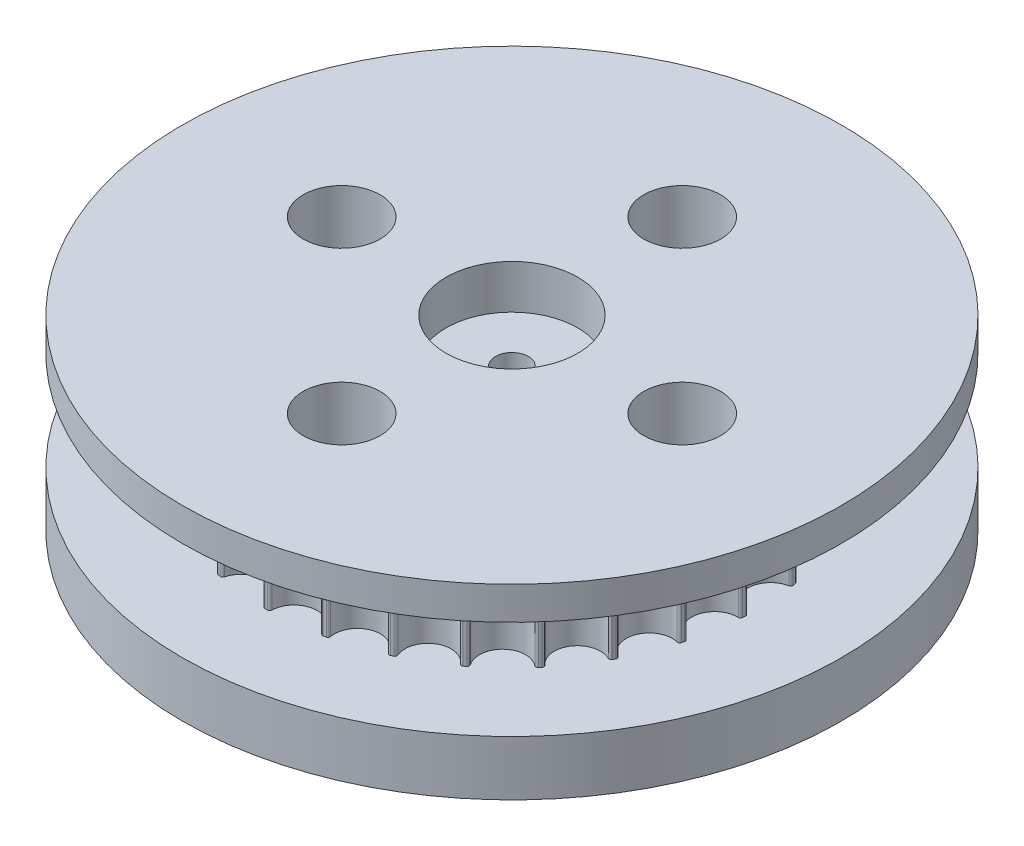
SolidWorks part; units mm, degrees
ref_plane "Front" through (0, 0, 0) normal (0, 0, 1) x (1, 0, 0)
ref_plane "Top" through (0, 0, 0) normal (0, 1, 0) x (1, 0, 0)
ref_plane "Right" through (0, 0, 0) normal (1, 0, 0) x (0, 0, -1)
sketch "Sketch1" plane through (0, 0, 0) normal (0, 1, 0) x (1, 0, 0)
  line L0 (0, 0) -> (0, 15.5) construction
  line L1 (0, 0) -> (15.5, 0) construction
  line L2 (0, 0) -> (0, -15.5) construction
  line L3 (0, 0) -> (-15.5, 0) construction
  circle A0 centre (0, 0) radius 30
  circle A1 centre (0, 0) radius 15.5 construction
  circle A2 centre (0, 15.5) radius 1.5
  circle A3 centre (15.5, 0) radius 1.5
  circle A4 centre (0, -15.5) radius 1.5
  circle A5 centre (-15.5, 0) radius 1.5
  circle A6 centre (0, 0) radius 1.5
  point P14 (0, 0)
  dimension "D1" = 60
  dimension "D2" = 31
  dimension "D3" = 3
  dimension "D5" = 3
  dimension "D4" = 4
extrude "Boss-Extrude1" add sketch "Sketch1" along normal blind 5
sketch "Sketch2" plane through (0, 5, 0) normal (0, 1, 0) x (1, 0, 0)
  line L0 (0, 0) -> (0, 15.5) construction
  line L1 (0, 0) -> (15.5, 0) construction
  line L2 (0, 0) -> (0, -15.5) construction
  line L3 (0, 0) -> (-15.5, 0) construction
  line L4 (0, 0) -> (0, 22.3727) construction
  line L5 (0, 0) -> (4.9707, 22.5821) construction
  line L6 (0, 0) -> (9.709, 20.9856) construction
  line L7 (0, 0) -> (13.9932, 18.4078) construction
  line L8 (0, 0) -> (17.6232, 14.9693) construction
  line L9 (0, 0) -> (20.4292, 10.8309) construction
  line L10 (0, 0) -> (22.2798, 6.186) construction
  line L11 (0, 0) -> (23.0888, 1.2518) construction
  line L12 (0, 0) -> (22.8181, -3.7408) construction
  line L13 (0, 0) -> (21.4804, -8.5586) construction
  line L14 (0, 0) -> (19.1384, -12.9761) construction
  line L15 (0, 0) -> (15.9014, -16.787) construction
  line L16 (0, 0) -> (11.921, -19.8128) construction
  line L17 (0, 0) -> (7.3831, -21.9123) construction
  line L18 (0, 0) -> (2.5, -22.9871) construction
  line L19 (0, 0) -> (-2.5, -22.9871) construction
  line L20 (0, 0) -> (-7.3831, -21.9123) construction
  line L21 (0, 0) -> (-11.921, -19.8128) construction
  line L22 (0, 0) -> (-15.9014, -16.787) construction
  line L23 (0, 0) -> (-19.1384, -12.9761) construction
  line L24 (0, 0) -> (-21.4804, -8.5586) construction
  line L25 (0, 0) -> (-22.0779, -3.6195) construction
  line L26 (0, 0) -> (-23.0888, 1.2518) construction
  line L27 (0, 0) -> (-22.2798, 6.186) construction
  line L28 (0, 0) -> (-20.4292, 10.8309) construction
  line L29 (0, 0) -> (-17.6232, 14.9693) construction
  line L30 (0, 0) -> (-13.9932, 18.4078) construction
  line L31 (0, 0) -> (-9.709, 20.9856) construction
  line L32 (0, 0) -> (-4.9707, 22.5821) construction
  line L33 (2.2986, 22.2543) -> (2.5392, 22.2281)
  line L34 (7.0288, 21.2399) -> (7.2582, 21.1626)
  line L35 (11.4304, 19.2323) -> (11.6379, 19.1075)
  line L36 (15.2976, 16.3255) -> (15.4733, 16.159)
  line L37 (18.4494, 12.6552) -> (18.5853, 12.4549)
  line L38 (20.7386, 8.3933) -> (20.8282, 8.1684)
  line L39 (22.058, 3.7389) -> (22.0972, 3.5)
  line L40 (22.3461, -1.0904) -> (22.333, -1.3321)
  line L41 (21.5892, -5.8686) -> (21.5245, -6.1019)
  line L42 (19.8229, -10.3725) -> (19.7095, -10.5863)
  line L43 (17.1297, -14.3913) -> (16.973, -14.5758)
  line L44 (13.6355, -17.7372) -> (13.4428, -17.8837)
  line L45 (9.5037, -20.2538) -> (9.2841, -20.3554)
  line L46 (4.9276, -21.8233) -> (4.6912, -21.8753)
  line L47 (0.121, -22.3723) -> (-0.121, -22.3723)
  line L48 (-4.6912, -21.8753) -> (-4.9276, -21.8233)
  line L49 (-9.2841, -20.3554) -> (-9.5037, -20.2538)
  line L50 (-13.4428, -17.8837) -> (-13.6355, -17.7372)
  line L51 (-16.973, -14.5758) -> (-17.1297, -14.3913)
  line L52 (-19.7095, -10.5863) -> (-19.8229, -10.3725)
  line L53 (-21.5245, -6.1019) -> (-21.5892, -5.8686)
  line L54 (-22.333, -1.3321) -> (-22.3461, -1.0904)
  line L55 (-22.0972, 3.5) -> (-22.058, 3.7389)
  line L56 (-20.8282, 8.1684) -> (-20.7386, 8.3933)
  line L57 (-18.5853, 12.4549) -> (-18.4494, 12.6552)
  line L58 (-15.4733, 16.159) -> (-15.2976, 16.3255)
  line L59 (-11.6379, 19.1075) -> (-11.4304, 19.2323)
  line L60 (-7.2582, 21.1626) -> (-7.0288, 21.2399)
  line L61 (-2.5392, 22.2281) -> (-2.2986, 22.2543)
  line L62 (0, 22.3727) -> (0, 23.8727) construction
  line L63 (4.8095, 21.8496) -> (4.9707, 22.5821) construction
  circle A0 centre (0, 15.5) radius 1.5
  circle A1 centre (0, 15.5) radius 1.5 construction
  circle A2 centre (15.5, 0) radius 1.5
  circle A3 centre (0, -15.5) radius 1.5
  circle A4 centre (-15.5, 0) radius 1.5
  circle A5 centre (0, 0) radius 20.2727 construction
  circle A6 centre (0, 0) radius 23.8727 construction
  circle A7 centre (0, 0) radius 22.3727 construction
  arc A8 (-2.0977, 22.2741) -> (2.0977, 22.2741) centre (0, 22.3727) ccw construction
  arc A9 (-2.2986, 22.2543) -> (-2.0799, 22.0829) centre (-2.278, 22.0553) cw
  arc A10 (2.2986, 22.2543) -> (2.0799, 22.0829) centre (2.278, 22.0553) ccw
  arc A11 (-2.0799, 22.0829) -> (2.0799, 22.0829) centre (0, 22.3727) ccw
  arc A12 (2.5392, 22.2281) -> (2.7159, 22.0138) centre (2.5165, 22.0294) cw
  arc A13 (2.7159, 22.0138) -> (6.7785, 21.1195) centre (4.8095, 21.8496) ccw
  arc A14 (7.0288, 21.2399) -> (6.7785, 21.1195) centre (6.966, 21.05) ccw
  arc A15 (7.2582, 21.1626) -> (7.3847, 20.9153) centre (7.1933, 20.9734) cw
  arc A16 (7.3847, 20.9153) -> (11.1601, 19.1686) centre (9.394, 20.3049) ccw
  arc A17 (11.4304, 19.2323) -> (11.1601, 19.1686) centre (11.3283, 19.0604) ccw
  arc A18 (11.6379, 19.1075) -> (11.7082, 18.8388) centre (11.5338, 18.9367) cw
  arc A19 (11.7082, 18.8388) -> (15.0198, 16.3214) centre (13.5394, 17.8107) ccw
  arc A20 (15.2976, 16.3255) -> (15.0198, 16.3214) centre (15.1608, 16.1795) ccw
  arc A21 (15.4733, 16.159) -> (15.4843, 15.8814) centre (15.335, 16.0145) cw
  arc A22 (15.4843, 15.8814) -> (18.1773, 12.711) centre (17.0516, 14.4838) ccw
  arc A23 (18.4494, 12.6552) -> (18.1773, 12.711) centre (18.2845, 12.5421) ccw
  arc A24 (18.5853, 12.4549) -> (18.5363, 12.1815) centre (18.4191, 12.3435) cw
  arc A25 (18.5363, 12.1815) -> (20.4848, 8.5062) centre (19.7665, 10.4795) ccw
  arc A26 (20.7386, 8.3933) -> (20.4848, 8.5062) centre (20.5532, 8.3183) ccw
  arc A27 (20.8282, 8.1684) -> (20.7216, 7.9119) centre (20.642, 8.0954) cw
  arc A28 (20.7216, 7.9119) -> (21.8344, 3.9037) centre (21.5572, 5.9853) ccw
  arc A29 (22.058, 3.7389) -> (21.8344, 3.9037) centre (21.8608, 3.7055) ccw
  arc A30 (22.0972, 3.5) -> (21.9379, 3.2724) centre (21.8997, 3.4687) cw
  arc A31 (21.9379, 3.2724) -> (22.1631, -0.8813) centre (22.3399, 1.2112) ccw
  arc A32 (22.3461, -1.0904) -> (22.1631, -0.8813) centre (22.1463, -1.0806) ccw
  arc A33 (22.333, -1.3321) -> (22.1285, -1.5201) centre (22.1333, -1.3202) cw
  arc A34 (22.1285, -1.5201) -> (21.4555, -5.6251) centre (22.0779, -3.6195) ccw
  arc A35 (21.5892, -5.8686) -> (21.4555, -5.6251) centre (21.3963, -5.8162) ccw
  arc A36 (21.5245, -6.1019) -> (21.2844, -6.2415) centre (21.3321, -6.0473) cw
  arc A37 (21.2844, -6.2415) -> (19.7447, -10.1059) centre (20.7837, -8.281) ccw
  arc A38 (19.8229, -10.3725) -> (19.7447, -10.1059) centre (19.6457, -10.2797) ccw
  arc A39 (19.7095, -10.5863) -> (19.445, -10.6711) centre (19.5333, -10.4917) cw
  arc A40 (19.445, -10.6711) -> (17.1106, -14.1142) centre (18.5176, -12.5553) ccw
  arc A41 (17.1297, -14.3913) -> (17.1106, -14.1142) centre (16.9766, -14.2626) ccw
  arc A42 (16.973, -14.5758) -> (16.6964, -14.6017) centre (16.8213, -14.4455) cw
  arc A43 (16.6964, -14.6017) -> (13.6764, -17.4625) centre (15.3857, -16.2425) ccw
  arc A44 (13.6355, -17.7372) -> (13.6764, -17.4625) centre (13.5136, -17.5787) ccw
  arc A45 (13.4428, -17.8837) -> (13.1671, -17.8496) centre (13.3226, -17.7238) cw
  arc A46 (13.1671, -17.8496) -> (9.6027, -19.9942) centre (11.5343, -19.1702) ccw
  arc A47 (9.5037, -20.2538) -> (9.6027, -19.9942) centre (9.4188, -20.0727) ccw
  arc A48 (9.2841, -20.3554) -> (9.0222, -20.2628) centre (9.2011, -20.1734) cw
  arc A49 (9.0222, -20.2628) -> (5.0801, -21.5911) centre (7.1436, -21.2015) ccw
  arc A50 (4.9276, -21.8233) -> (5.0801, -21.5911) centre (4.8835, -21.6282) ccw
  arc A51 (4.6912, -21.8753) -> (4.4553, -21.7286) centre (4.6493, -21.6798) cw
  arc A52 (4.4553, -21.7286) -> (0.3199, -22.1784) centre (2.4189, -22.2415) ccw
  arc A53 (0.121, -22.3723) -> (0.3199, -22.1784) centre (0.12, -22.1723) ccw
  arc A54 (-0.121, -22.3723) -> (-0.3199, -22.1784) centre (-0.12, -22.1723) cw
  arc A55 (-0.3199, -22.1784) -> (-4.4553, -21.7286) centre (-2.4189, -22.2415) ccw
  arc A56 (-4.6912, -21.8753) -> (-4.4553, -21.7286) centre (-4.6493, -21.6798) ccw
  arc A57 (-4.9276, -21.8233) -> (-5.0801, -21.5911) centre (-4.8835, -21.6282) cw
  arc A58 (-5.0801, -21.5911) -> (-9.0222, -20.2628) centre (-7.1436, -21.2015) ccw
  arc A59 (-9.2841, -20.3554) -> (-9.0222, -20.2628) centre (-9.2011, -20.1734) ccw
  arc A60 (-9.5037, -20.2538) -> (-9.6027, -19.9942) centre (-9.4188, -20.0727) cw
  arc A61 (-9.6027, -19.9942) -> (-13.1671, -17.8496) centre (-11.5343, -19.1702) ccw
  arc A62 (-13.4428, -17.8837) -> (-13.1671, -17.8496) centre (-13.3226, -17.7238) ccw
  arc A63 (-13.6355, -17.7372) -> (-13.6764, -17.4625) centre (-13.5136, -17.5787) cw
  arc A64 (-13.6764, -17.4625) -> (-16.6964, -14.6017) centre (-15.3857, -16.2425) ccw
  arc A65 (-16.973, -14.5758) -> (-16.6964, -14.6017) centre (-16.8213, -14.4455) ccw
  arc A66 (-17.1297, -14.3913) -> (-17.1106, -14.1142) centre (-16.9766, -14.2626) cw
  arc A67 (-17.1106, -14.1142) -> (-19.445, -10.6711) centre (-18.5176, -12.5553) ccw
  arc A68 (-19.7095, -10.5863) -> (-19.445, -10.6711) centre (-19.5333, -10.4917) ccw
  arc A69 (-19.8229, -10.3725) -> (-19.7447, -10.1059) centre (-19.6457, -10.2797) cw
  arc A70 (-19.7447, -10.1059) -> (-21.2844, -6.2415) centre (-20.7837, -8.281) ccw
  arc A71 (-21.5245, -6.1019) -> (-21.2844, -6.2415) centre (-21.3321, -6.0473) ccw
  arc A72 (-21.5892, -5.8686) -> (-21.4555, -5.6251) centre (-21.3963, -5.8162) cw
  arc A73 (-21.4555, -5.6251) -> (-22.1285, -1.5201) centre (-22.0779, -3.6195) ccw
  arc A74 (-22.333, -1.3321) -> (-22.1285, -1.5201) centre (-22.1333, -1.3202) ccw
  arc A75 (-22.3461, -1.0904) -> (-22.1631, -0.8813) centre (-22.1463, -1.0806) cw
  arc A76 (-22.1631, -0.8813) -> (-21.9379, 3.2724) centre (-22.3399, 1.2112) ccw
  arc A77 (-22.0972, 3.5) -> (-21.9379, 3.2724) centre (-21.8997, 3.4687) ccw
  arc A78 (-22.058, 3.7389) -> (-21.8344, 3.9037) centre (-21.8608, 3.7055) cw
  arc A79 (-21.8344, 3.9037) -> (-20.7216, 7.9119) centre (-21.5572, 5.9853) ccw
  arc A80 (-20.8282, 8.1684) -> (-20.7216, 7.9119) centre (-20.642, 8.0954) ccw
  arc A81 (-20.7386, 8.3933) -> (-20.4848, 8.5062) centre (-20.5532, 8.3183) cw
  arc A82 (-20.4848, 8.5062) -> (-18.5363, 12.1815) centre (-19.7665, 10.4795) ccw
  arc A83 (-18.5853, 12.4549) -> (-18.5363, 12.1815) centre (-18.4191, 12.3435) ccw
  arc A84 (-18.4494, 12.6552) -> (-18.1773, 12.711) centre (-18.2845, 12.5421) cw
  arc A85 (-18.1773, 12.711) -> (-15.4843, 15.8814) centre (-17.0516, 14.4838) ccw
  arc A86 (-15.4733, 16.159) -> (-15.4843, 15.8814) centre (-15.335, 16.0145) ccw
  arc A87 (-15.2976, 16.3255) -> (-15.0198, 16.3214) centre (-15.1608, 16.1795) cw
  arc A88 (-15.0198, 16.3214) -> (-11.7082, 18.8388) centre (-13.5394, 17.8107) ccw
  arc A89 (-11.6379, 19.1075) -> (-11.7082, 18.8388) centre (-11.5338, 18.9367) ccw
  arc A90 (-11.4304, 19.2323) -> (-11.1601, 19.1686) centre (-11.3283, 19.0604) cw
  arc A91 (-11.1601, 19.1686) -> (-7.3847, 20.9153) centre (-9.394, 20.3049) ccw
  arc A92 (-7.2582, 21.1626) -> (-7.3847, 20.9153) centre (-7.1933, 20.9734) ccw
  arc A93 (-7.0288, 21.2399) -> (-6.7785, 21.1195) centre (-6.966, 21.05) cw
  arc A94 (-6.7785, 21.1195) -> (-2.7159, 22.0138) centre (-4.8095, 21.8496) ccw
  arc A95 (-2.5392, 22.2281) -> (-2.7159, 22.0138) centre (-2.5165, 22.0294) ccw
  circle A96 centre (0, 0) radius 23.1227 construction
  point P16 (0, 0)
  point P19 (0, 23.1227)
  point P255 (0, 0)
  point P312 (0, 0)
  dimension "D2" = 2.1
  dimension "D3" = 3.6
  dimension "D4" = 0.2
  dimension "D6" = 5
  dimension "D1" = 4
  dimension "D5" = 29
  dimension "D7" = 29
extrude "Boss-Extrude2" add sketch "Sketch2" along normal blind 9
sketch "Sketch3" plane through (0, 14, 0) normal (0, 1, 0) x (1, 0, 0)
  line L0 (0, 15.5) -> (0, 0) construction
  line L1 (15.5, 0) -> (0, 0) construction
  line L2 (0, -15.5) -> (0, 0) construction
  line L3 (-15.5, 0) -> (0, 0) construction
  circle A0 centre (0, 15.5) radius 1.5
  circle A1 centre (0, 15.5) radius 1.5 construction
  circle A2 centre (15.5, 0) radius 1.5
  circle A3 centre (0, -15.5) radius 1.5
  circle A4 centre (-15.5, 0) radius 1.5
  circle A5 centre (0, 0) radius 30
  circle A6 centre (0, 0) radius 30 construction
  point P15 (0, 0)
  dimension "D1" = 4
extrude "Boss-Extrude3" add sketch "Sketch3" along normal blind 3
sketch "Sketch4" plane through (0, 17, 0) normal (0, 1, 0) x (1, 0, 0)
  circle A0 centre (0, 0) radius 6
  dimension "D1" = 12
extrude "Cut-Extrude1" cut sketch "Sketch4" against normal blind 4
sketch "Sketch5" plane through (0, 5, 0) normal (0, -1, 0) x (1, 0, 0)
  circle A0 centre (0, 0) radius 1.5
  circle A1 centre (0, 0) radius 1.5 construction
extrude "Cut-Extrude2" cut sketch "Sketch5" against normal through all
sketch "Sketch6" plane through (0, 17, 0) normal (0, 1, 0) x (1, 0, 0)
  line L0 (0, 0) -> (15.5, 0) construction
  line L1 (0, 0) -> (0, -15.5) construction
  line L2 (0, 0) -> (-15.5, 0) construction
  line L3 (0, 0) -> (0, 15.5) construction
  circle A0 centre (15.5, 0) radius 3.5
  circle A1 centre (15.5, 0) radius 1.5 construction
  circle A2 centre (0, -15.5) radius 3.5
  circle A3 centre (-15.5, 0) radius 3.5
  circle A4 centre (0, 15.5) radius 3.5
  point P16 (0, 0)
  dimension "D1" = 7
  dimension "D2" = 4
extrude "Cut-Extrude3" cut sketch "Sketch6" against normal blind 5
